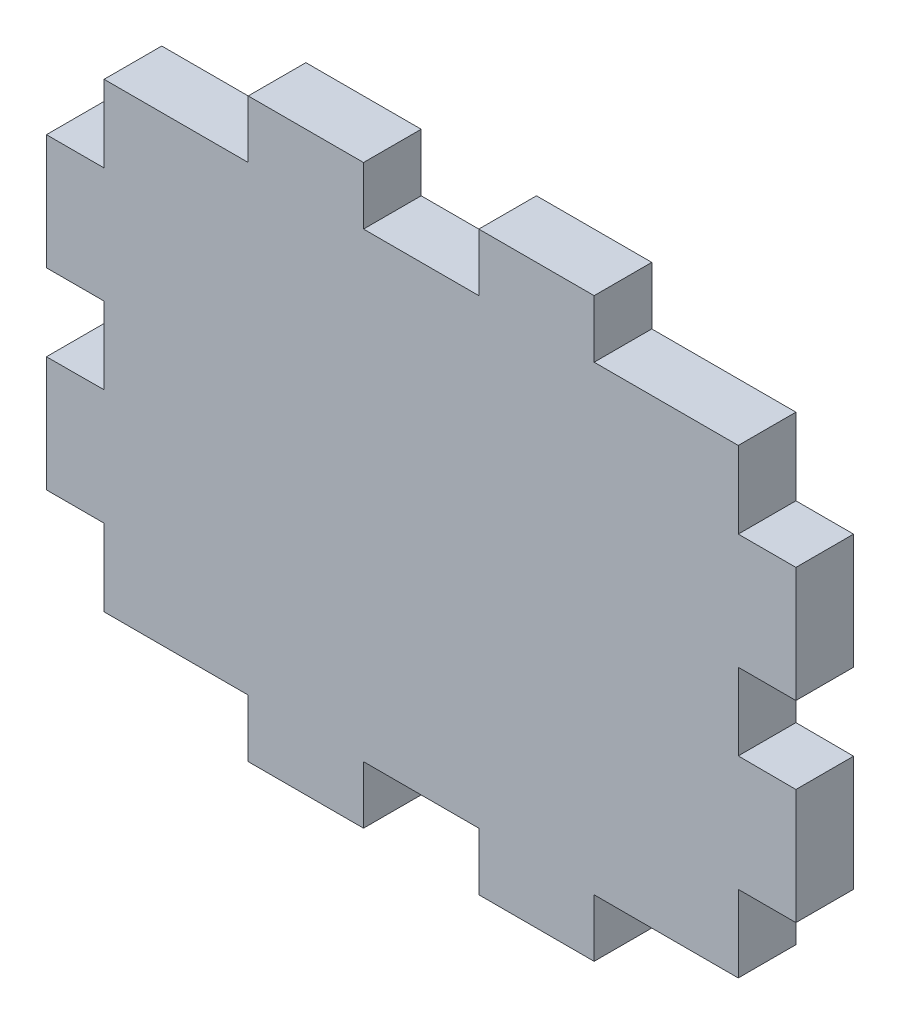
SolidWorks part; units mm, degrees
material "Beech"
ref_plane "Front" through (0, 0, 0) normal (0, 0, 1) x (1, 0, 0)
ref_plane "Top" through (0, 0, 0) normal (0, 1, 0) x (1, 0, 0)
ref_plane "Right" through (0, 0, 0) normal (1, 0, 0) x (0, 0, -1)
sketch "Sketch1" plane through (0, 0, 0) normal (0, 0, 1) x (1, 0, 0)
  line L0 (-7.5, -10) -> (-7.5, -12.5)
  line L1 (-13.75, -10) -> (13.75, -10)
  line L2 (-13.75, -10) -> (-13.75, 10) construction
  line L3 (-13.75, 10) -> (13.75, 10)
  line L4 (13.75, -10) -> (13.75, 10) construction
  line L5 (-13.75, -10) -> (13.75, 10) construction
  line L6 (-13.75, 10) -> (13.75, -10) construction
  line L7 (2.5, 10) -> (7.5, 10)
  line L8 (2.5, 10) -> (2.5, 12.5)
  line L9 (2.5, 12.5) -> (7.5, 12.5)
  line L10 (7.5, 10) -> (7.5, 12.5)
  line L11 (2.5, 10) -> (7.5, 12.5) construction
  line L12 (2.5, 12.5) -> (7.5, 10) construction
  line L13 (2.5, -10) -> (7.5, -10)
  line L14 (2.5, -10) -> (2.5, -12.5)
  line L15 (2.5, -12.5) -> (7.5, -12.5)
  line L16 (7.5, -10) -> (7.5, -12.5)
  line L17 (2.5, -10) -> (7.5, -12.5) construction
  line L18 (2.5, -12.5) -> (7.5, -10) construction
  line L19 (-7.5, -10) -> (-2.5, -10)
  line L20 (-2.5, -10) -> (-2.5, -12.5)
  line L21 (-7.5, -12.5) -> (-2.5, -12.5)
  line L30 (-7.5, 10) -> (-7.5, 12.5)
  line L31 (-7.5, 10) -> (-2.5, 10)
  line L32 (-2.5, 10) -> (-2.5, 12.5)
  line L33 (-7.5, 12.5) -> (-2.5, 12.5)
  line L42 (-27.5, 10) -> (-27.5, 12.5) [skipped]
  line L43 (-27.5, 12.5) -> (-22.5, 12.5) [skipped]
  line L44 (-22.5, 10) -> (-22.5, 12.5) [skipped]
  line L45 (-27.5, 10) -> (-22.5, 10) [skipped]
  line L46 (-17.5, 10) -> (-17.5, 12.5) [skipped]
  line L47 (-17.5, 12.5) -> (-12.5, 12.5) [skipped]
  line L48 (-12.5, 10) -> (-12.5, 12.5) [skipped]
  line L49 (-17.5, 10) -> (-12.5, 10) [skipped]
  line L50 (-27.5, -10) -> (-27.5, -12.5) [skipped]
  line L51 (-27.5, -12.5) -> (-22.5, -12.5) [skipped]
  line L52 (-22.5, -10) -> (-22.5, -12.5) [skipped]
  line L53 (-27.5, -10) -> (-22.5, -10) [skipped]
  line L54 (-17.5, -10) -> (-17.5, -12.5) [skipped]
  line L55 (-17.5, -12.5) -> (-12.5, -12.5) [skipped]
  line L56 (-12.5, -10) -> (-12.5, -12.5) [skipped]
  line L57 (-17.5, -10) -> (-12.5, -10) [skipped]
  line L58 (0, 5.4028) -> (0, -4.5111) construction
  line L59 (-13.75, 10) -> (-13.75, 6.67)
  line L60 (-13.75, 6.67) -> (-16.25, 6.67)
  line L61 (-16.25, 6.67) -> (-16.25, 1.67)
  line L62 (-16.25, 1.67) -> (-13.75, 1.67)
  line L63 (-13.75, 1.67) -> (-13.75, -1.66)
  line L64 (-13.75, -1.66) -> (-16.25, -1.67)
  line L65 (-16.25, -1.67) -> (-16.25, -6.67)
  line L66 (-16.25, -6.67) -> (-13.75, -6.67)
  line L67 (-13.75, -6.67) -> (-13.75, -10)
  line L76 (13.75, -6.67) -> (13.75, -10)
  line L77 (16.25, -6.67) -> (13.75, -6.67)
  line L78 (16.25, -1.67) -> (16.25, -6.67)
  line L79 (13.75, -1.66) -> (16.25, -1.67)
  line L80 (13.75, 1.67) -> (13.75, -1.66)
  line L81 (16.25, 1.67) -> (13.75, 1.67)
  line L82 (16.25, 6.67) -> (16.25, 1.67)
  line L83 (13.75, 6.67) -> (16.25, 6.67)
  line L84 (13.75, 10) -> (13.75, 6.67)
  point P0 (0, 0)
  point P2 (-13.75, -5.7305)
  point P10 (5, 11.25)
  point P16 (5, -11.25)
  point P28 (0, 0)
  point P39 (-13.75, -6.5461)
  point P40 (0, 0)
  point P73 (-15, -6.67)
  dimension "D1" = 20
  dimension "D2" = 27.5
  dimension "D3" = 6.25
  dimension "D4" = 2.5
  dimension "D5" = 5
  dimension "D6" = 6.25
  dimension "D7" = 5
  dimension "D8" = 2.5
  dimension "D11" = 5
  dimension "D12" = 5
  dimension "D13" = 3.33
  dimension "D14" = 5
  dimension "D15" = 2.5
  dimension "D9" = 4
  dimension "D10" = 4
extrude "Boss-Extrude1" add sketch "Sketch1" along normal blind 2.5
